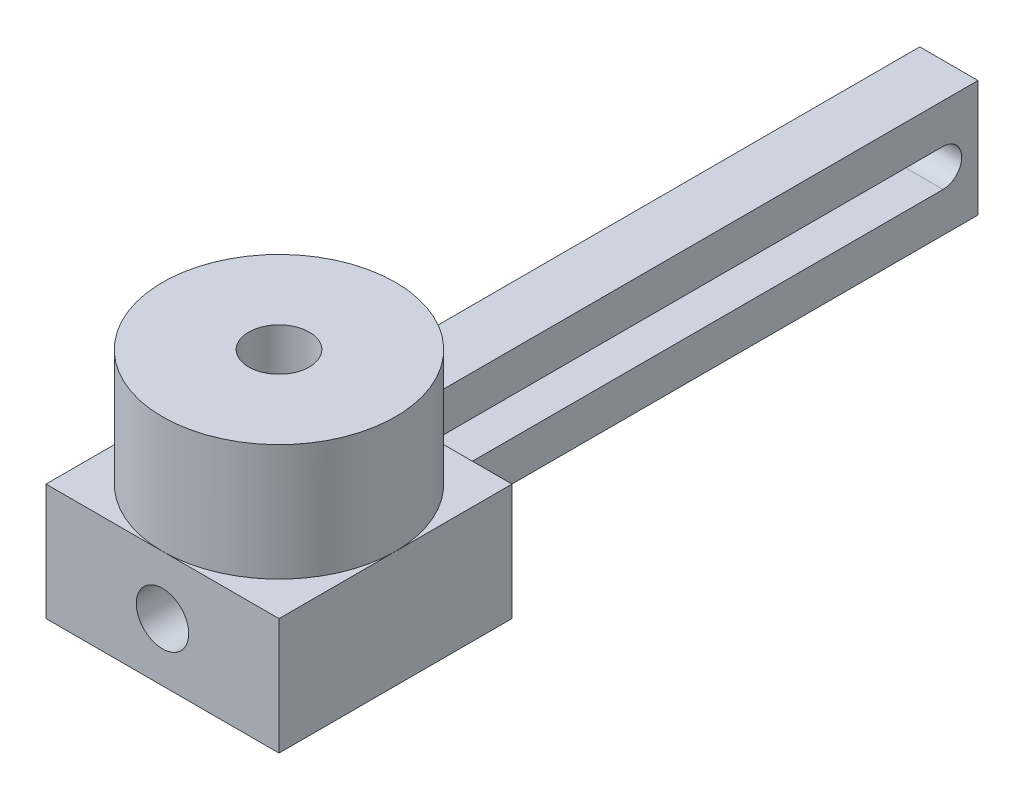
SolidWorks part; units mm, degrees
ref_plane "前视基准面" through (0, 0, 0) normal (0, 0, 1) x (1, 0, 0)
ref_plane "上视基准面" through (0, 0, 0) normal (0, 1, 0) x (1, 0, 0)
ref_plane "右视基准面" through (0, 0, 0) normal (1, 0, 0) x (0, 0, -1)
other "Configuration Table"
sketch "草图3" plane through (0, 0, 0) normal (0, 1, 0) x (1, 0, 0)
  line L1 (-5, -30) -> (5, -30)
  line L2 (-5, -30) -> (-5, 30)
  line L3 (-5, 30) -> (5, 30)
  line L4 (5, -30) -> (5, 30)
  line L5 (-5, -30) -> (5, 30) construction
  line L6 (-5, 30) -> (5, -30) construction
  point P0 (0, 0)
  dimension "D1" = 60
  dimension "D2" = 10
extrude "凸台-拉伸3" add sketch "草图3" along normal blind 10
sketch "草图4" plane through (0, 0, 0) normal (0, 1, 0) x (1, 0, 0)
  line L0 (0, -42.7601) -> (0, 35.0047) construction
  line L1 (-5, -30) -> (5, -30) construction
  circle A0 centre (0, -30) radius 10
  circle A1 centre (0, -30) radius 2.6
  dimension "D1" = 20
  dimension "D2" = 5.2
extrude "凸台-拉伸4" add sketch "草图4" along normal blind 20
sketch "草图6" plane through (0, 10, 0) normal (0, 1, 0) x (1, 0, 0)
  line L1 (5, 30) -> (-5, 30) construction
  line L2 (0, 30) -> (6, 30)
  line L3 (0, 30) -> (0, -20)
  line L4 (0, -20) -> (6, -20)
  line L5 (6, 30) -> (6, -20)
  dimension "D1" = 6
  dimension "D2" = 50
extrude "切除-拉伸2" cut sketch "草图6" against normal through all
sketch "草图7" plane through (-5, 0, 0) normal (-1, 0, 0) x (0, 0, 1)
  line L0 (-38.2722, 0) -> (48.1271, 0) construction
  line L1 (-38.2722, 5) -> (48.1271, 5) construction
  line L3 (-30, -8.3311) -> (-30, 16.6689) construction
  line L5 (-27, -8.3311) -> (-27, 16.6689) construction
  line L6 (16, -8.3311) -> (16, 16.6689) construction
  line L11 (0, 15.4441) -> (0, -13.0007) construction
  line L14 (-27, 5) -> (16, 5) construction
  line L15 (-27, 6.6) -> (16, 6.6)
  line L16 (-27, 3.4) -> (16, 3.4)
  arc A2 (-27, 6.6) -> (-27, 3.4) centre (-27, 5) ccw
  arc A3 (16, 3.4) -> (16, 6.6) centre (16, 5) ccw
  point P34 (-5.5, 5)
  dimension "D4" = 3.2
  dimension "D5" = 30
  dimension "D1" = 5
  dimension "D2" = 3
  dimension "D3" = 46
extrude "切除-拉伸3" cut sketch "草图7" against normal through all
sketch "草图16" plane through (0, 0, 20) normal (0, 0, 1) x (1, 0, 0)
  line L0 (0, 23.4676) -> (0, -5.4026) construction
  line L1 (-10, 0) -> (10, 0)
  line L2 (-10, 10) -> (10, 10)
  line L3 (-10, 10) -> (-10, 0)
  line L4 (10, 10) -> (10, 0)
  line L6 (10, 23.4676) -> (10, -5.4026) construction
  line L7 (-10, 23.4676) -> (-10, -5.4026) construction
  line L8 (-14.6286, 0) -> (15.2091, 0) construction
  line L9 (-14.6286, 10) -> (15.2091, 10) construction
  dimension "D1" = 10
  dimension "D2" = 10
  dimension "D3" = 10
extrude "凸台-拉伸5" add sketch "草图16" along normal blind 20
sketch "草图5" plane through (0, 0, 0) normal (0, -1, 0) x (1, 0, 0)
  circle A0 centre (0, 30) radius 2.6 construction
  circle A1 centre (0, 30) radius 2.6
extrude "切除-拉伸1" cut sketch "草图5" against normal through all
sketch "草图18" plane through (0, 0, 40) normal (0, 0, 1) x (1, 0, 0)
  line L0 (0, 25.5574) -> (0, -3.7462) construction
  line L1 (-15.4286, 0) -> (17.6689, 0) construction
  line L3 (-15.4286, 5) -> (17.6689, 5) construction
  circle A0 centre (0, 5) radius 2.25
  dimension "D1" = 4.5
  dimension "D2" = 5
extrude "切除-拉伸4" cut sketch "草图18" against normal blind 10
